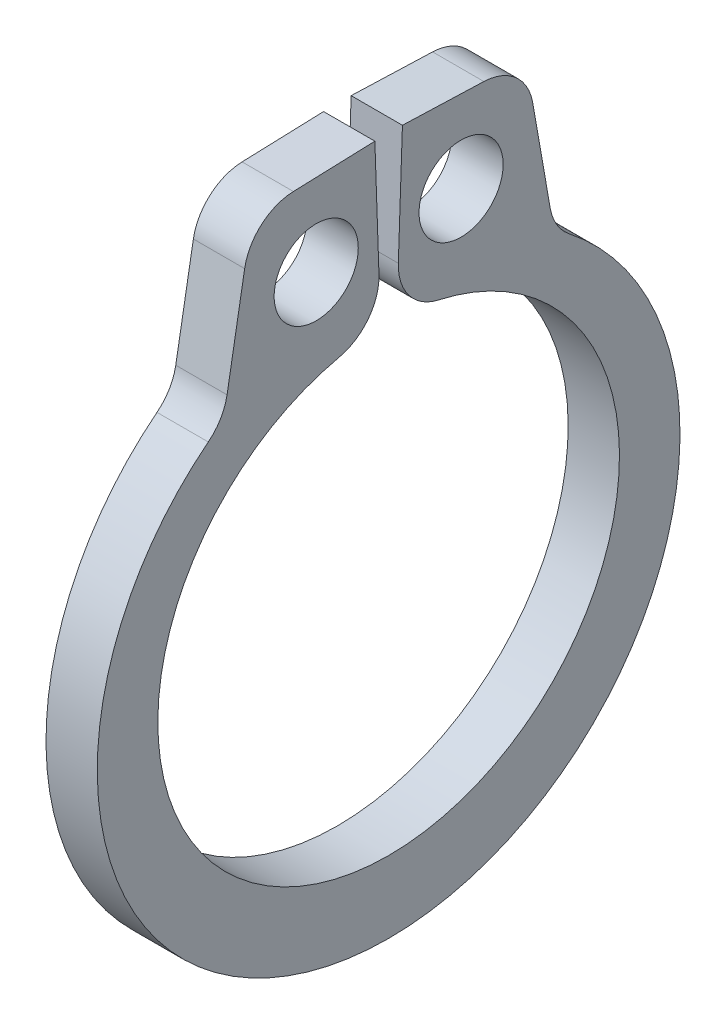
SolidWorks part; units mm, degrees
material "Cast Carbon Steel"
ref_plane "Front" through (0, 0, 0) normal (0, 0, 1) x (1, 0, 0)
ref_plane "Top" through (0, 0, 0) normal (0, 1, 0) x (1, 0, 0)
ref_plane "Right" through (0, 0, 0) normal (1, 0, 0) x (0, 0, -1)
sketch "Sketch1" plane through (0, 0, 0) normal (1, 0, 0) x (0, 0, -1)
  line L0 (0, 0) -> (0, 2.8575) construction
  line L1 (-0.0997, 2.8558) -> (-0.1706, 4.8865)
  line L2 (0.1706, 4.8865) -> (1.6937, 4.8333)
  line L3 (1.6937, 4.8333) -> (2.0442, 2.8318)
  line L4 (0.0997, 2.8558) -> (0.1706, 4.8865)
  line L5 (-0.1706, 4.8865) -> (-1.6937, 4.8333)
  line L6 (-1.6937, 4.8333) -> (-2.0442, 2.8318)
  line L7 (-2.0442, 2.8318) -> (-1.6725, 2.3169) construction
  line L8 (2.0442, 2.8318) -> (1.6725, 2.3169) construction
  line L9 (0, -2.8575) -> (0, -3.7465) construction
  line L10 (-1.6937, 4.8333) -> (-0.0997, 2.8558) construction
  line L11 (0, 2.8575) -> (0, 4.8895) construction
  line L12 (-2.8575, 0) -> (2.8575, 0) construction
  circle A0 centre (0, 0) radius 2.8575 construction
  arc A1 (-0.0997, 2.8558) -> (0.0997, 2.8558) centre (0, 0) ccw
  circle A4 centre (-0.8967, 3.8445) radius 0.5207
  circle A5 centre (0.8967, 3.8445) radius 0.5207
  arc A6 (-2.0442, 2.8318) -> (2.0442, 2.8318) centre (0, -0.1398) ccw construction
  point P0 (0, -3.7465)
  dimension "Ring ID" = 5.715
  dimension "Hole Diameter" = 1.0414
  dimension "Min. Sec." = 0.635
  dimension "Max. Sec." = 0.889
  dimension "Lug Height" = 2.032
  dimension "D2" = 1.524
  dimension "Angle" = 2
sketch "Sketch2" plane through (0, 0, 0) normal (0, 1, 0) x (1, 0, 0)
  line L0 (-0.3175, -3.604) -> (0.3175, -3.604) construction
  line L1 (0, -3.6067) -> (0, 3.6067) construction
  point P8 (0, -3.604)
  dimension "Ring Thickness" = 0.635
sketch "Sketch3" plane through (0, 0, 0) normal (1, 0, 0) x (0, 0, -1)
  line L0 (-1.6937, 4.8333) -> (-2.0442, 2.8318) construction
  line L1 (-1.6937, 4.8333) -> (-2.0442, 2.8318)
  line L2 (-0.1706, 4.8865) -> (-1.6937, 4.8333) construction
  line L3 (-0.1706, 4.8865) -> (-1.6937, 4.8333)
  line L4 (-0.0997, 2.8558) -> (-0.1706, 4.8865) construction
  line L5 (-0.0997, 2.8558) -> (-0.1706, 4.8865)
  line L6 (0.0997, 2.8558) -> (0.1706, 4.8865) construction
  line L7 (0.0997, 2.8558) -> (0.1706, 4.8865)
  line L8 (0.1706, 4.8865) -> (1.6937, 4.8333) construction
  line L9 (0.1706, 4.8865) -> (1.6937, 4.8333)
  line L10 (1.6937, 4.8333) -> (2.0442, 2.8318) construction
  line L11 (1.6937, 4.8333) -> (2.0442, 2.8318)
  arc A0 (-2.0442, 2.8318) -> (2.0442, 2.8318) centre (0, -0.1398) ccw construction
  arc A1 (-2.0442, 2.8318) -> (2.0442, 2.8318) centre (0, -0.1398) ccw
  arc A2 (-0.0997, 2.8558) -> (0.0997, 2.8558) centre (0, 0) ccw construction
  arc A3 (-0.0997, 2.8558) -> (0.0997, 2.8558) centre (0, 0) ccw
  circle A4 centre (-0.8967, 3.8445) radius 0.5207 construction
  circle A5 centre (-0.8967, 3.8445) radius 0.5207
  circle A6 centre (0.8967, 3.8445) radius 0.5207 construction
  circle A7 centre (0.8967, 3.8445) radius 0.5207
extrude "Boss-Extrude1" add sketch "Sketch3" along normal up to vertex (0.3175 mm away) and the other way up to vertex (0.3175 mm away) up to point (0.3175, 0, 3.604) other way up to point (-0.3175, 0, 3.604)
fillet "Fillet1" radius 0.635 6 edges at (0, 2.8318, -2.0442) (0, 4.8333, -1.6937) (0, 2.8558, -0.0997) (0, 2.8558, 0.0997) (0, 4.8333, 1.6937) (0, 2.8318, 2.0442)
sketch "Sketch4" plane through (0, 0, 0) normal (1, 0, 0) x (0, 0, -1)
  line L0 (-2.4747, 1.4288) -> (0, 0) construction
  line L1 (0, 0) -> (0, 2.8575) construction
  line L2 (0, 4.8895) -> (0, 2.8575) construction
  arc A0 (-0.0997, 2.8558) -> (0.0997, 2.8558) centre (0, 0) ccw construction
  point P0 (0, 0)
  point P1 (-2.4747, 1.4288)
  dimension "D1" = 60
equation "\"D2@Sketch1\" = \"Lug Height@Sketch1\" * .75"
